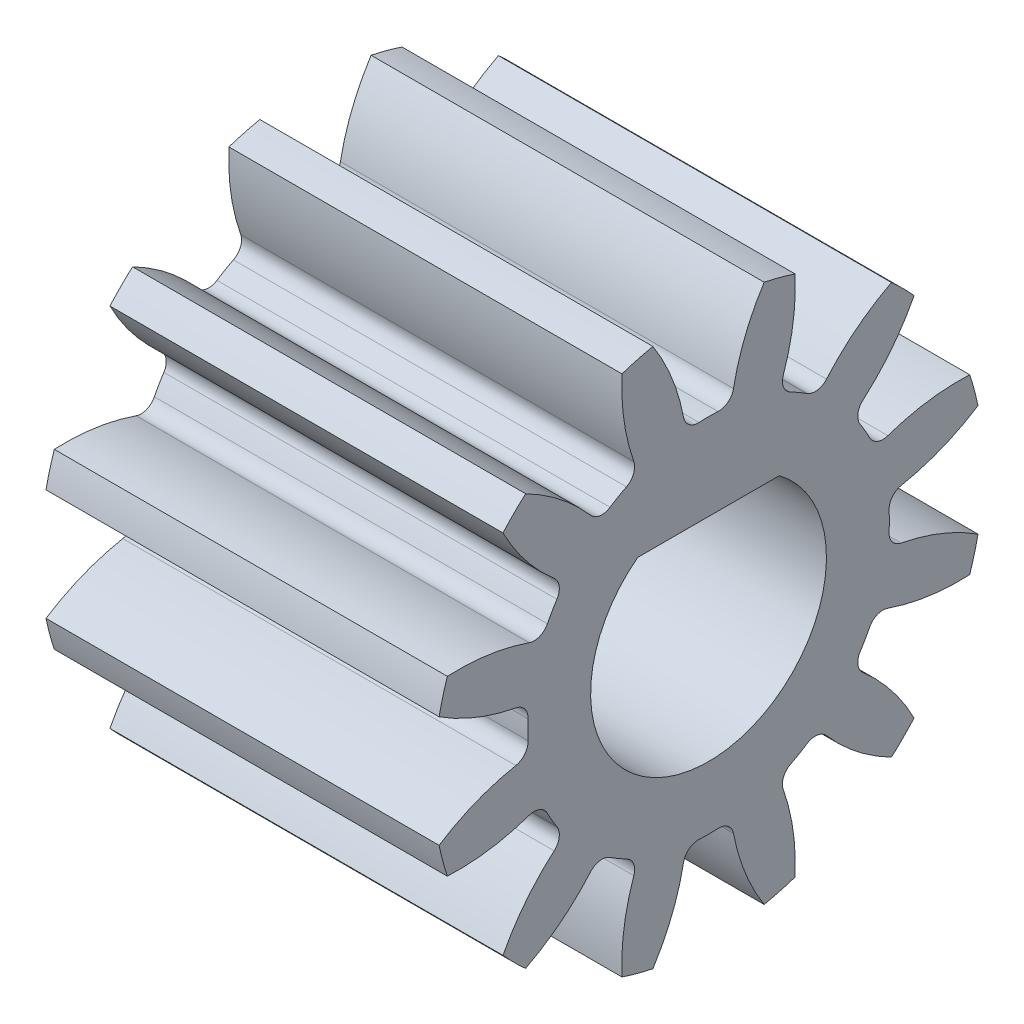
SolidWorks part; units mm, degrees
ref_plane "Front Plane" through (0, 0, 0) normal (0, 0, 1) x (1, 0, 0)
ref_plane "Top Plane" through (0, 0, 0) normal (0, 1, 0) x (1, 0, 0)
ref_plane "Right Plane" through (0, 0, 0) normal (1, 0, 0) x (0, 0, -1)
sketch "Sketch1" plane through (0, 0, 0) normal (1, 0, 0) x (0, 0, -1)
  circle A0 centre (0, 0) radius 3
  circle A1 centre (0, 0) radius 7
  dimension "D1" = 6
  dimension "D2" = 14
extrude "Boss-Extrude2" add sketch "Sketch1" along normal blind 10
sketch "Sketch3" plane through (10, 0, 0) normal (1, 0, 0) x (0, 0, -1)
  line L0 (0, 0) -> (0, 7) construction
  line L1 (-0.5809, 4.5632) -> (0, 0) construction
  line L2 (0, 3.3655) -> (-5.0896, 17.3489) construction
  circle A0 centre (0, 0) radius 7 construction
  arc A1 (0.5809, 4.5632) -> (-0.5809, 4.5632) centre (0, 0) ccw
  arc A2 (0.9354, 5.9266) -> (-0.9354, 5.9266) centre (0, 0) ccw construction
  arc A3 (1.4152, 6.8554) -> (-1.4152, 6.8554) centre (0, 0) ccw
  arc A4 (-1.4152, 6.8554) -> (-0.5809, 4.5632) centre (-6.0652, 3.865) cw
  arc A5 (1.4152, 6.8554) -> (0.5809, 4.5632) centre (6.0652, 3.865) ccw
  point P17 (-0.87, 5.7559)
  dimension "D1" = 14
  dimension "D2" = 12
  dimension "D3" = 2.4
  dimension "D4" = 20
  dimension "D5" = 1.8708
extrude "Cut-Extrude1" cut sketch "Sketch3" against normal through all
fillet "Fillet1" radius 0.38 2 edges at (5, 4.5632, -0.5809) (5, 4.5632, 0.5809)
pattern_circular "CirPattern2" count 12 over 360 about axis through (0, 0, 0) along (1, 0, 0) of "Fillet1", "Cut-Extrude1"
sketch "Sketch4" plane through (0, 0, 0) normal (-1, 0, 0) x (0, 0, 1)
  line L0 (0, -3) -> (3, -3) construction
  line L5 (-1.8, 2.4) -> (1.8, 2.4)
  circle A0 centre (0, 0) radius 3 construction
  arc A1 (-1.8, 2.4) -> (1.8, 2.4) centre (0, 0) cw
  dimension "D2" = 3
  dimension "D1" = 5.4
  dimension "D3" = 3.6
extrude "Boss-Extrude3" add sketch "Sketch4" against normal blind 10
equation "\"No of teeth\"= 12"
equation "\"Module\"= 1"
equation "\"Outer Diameter\"= ( \"No of teeth\" + 2 ) * \"Module\""
equation "\"Pitch Diameter\"= \"No of teeth\" * \"Module\""
equation "\"Backlash\"= 0.3 * \"Module\""
equation "\"Arc Length\"= ( ( \"Module\" * pi ) / 2 ) + \"Backlash\""
equation "\"Fillet Radius\"= 0.38 * \"Module\""
equation "\"Bore Diameter\"= 6"
equation "\"Presseure angle\"= 20"
equation "\"Tooth Design\"= IIF ( \"Module\" <= 1.25 , 2.4 * \"Module\" , 2.25 * \"Module\" )"
equation "\"D1@Sketch1\"=\"Bore Diameter\""
equation "\"D2@Sketch1\"=\"Outer Diameter\""
equation "\"D1@Sketch3\"=\"Outer Diameter\""
equation "\"D2@Sketch3\"=\"Pitch Diameter\""
equation "\"D3@Sketch3\"=\"Tooth Design\""
equation "\"D4@Sketch3\"=\"Presseure angle\""
equation "\"D5@Sketch3\"=\"Arc Length\""
equation "\"D1@Fillet1\"=\"Fillet Radius\""
equation "\"D1@CirPattern2\"=\"No of teeth\""
